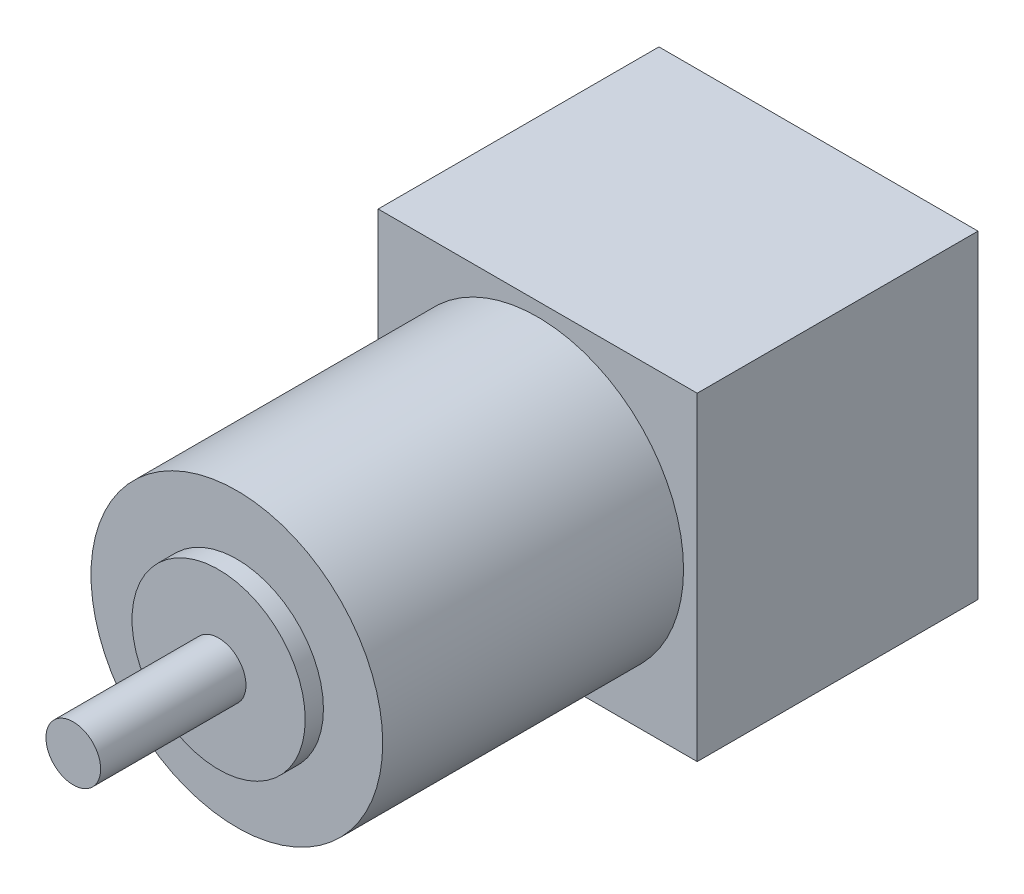
SolidWorks part; units mm, degrees
ref_plane "Front Plane" through (0, 0, 0) normal (0, 0, 1) x (1, 0, 0)
ref_plane "Top Plane" through (0, 0, 0) normal (0, 1, 0) x (1, 0, 0)
ref_plane "Right Plane" through (0, 0, 0) normal (1, 0, 0) x (0, 0, -1)
sketch "Sketch1" plane through (0, 0, 0) normal (0, 0, 1) x (1, 0, 0)
  line L1 (-17.5, -17.5) -> (17.5, -17.5)
  line L2 (-17.5, -17.5) -> (-17.5, 17.5)
  line L3 (-17.5, 17.5) -> (17.5, 17.5)
  line L4 (17.5, -17.5) -> (17.5, 17.5)
  line L5 (-17.5, -17.5) -> (17.5, 17.5) construction
  line L6 (-17.5, 17.5) -> (17.5, -17.5) construction
  point P0 (0, 0)
  dimension "D1" = 35
extrude "Boss-Extrude1" add sketch "Sketch1" along normal blind 30.8
sketch "Sketch2" plane through (0, 0, 30.8) normal (0, 0, 1) x (1, 0, 0)
  circle A0 centre (0, 0) radius 16
  dimension "D1" = 32
extrude "Boss-Extrude2" add sketch "Sketch2" along normal blind 33
sketch "Sketch4" plane through (0, 0, 63.8) normal (0, 0, 1) x (1, 0, 0)
  circle A0 centre (0, 0) radius 9.5
  dimension "D1" = 19
extrude "Boss-Extrude4" add sketch "Sketch4" along normal blind 2
sketch "Sketch3" plane through (0, 0, 65.8) normal (0, 0, 1) x (1, 0, 0)
  circle A0 centre (0, 0) radius 3
  dimension "D1" = 6
extrude "Boss-Extrude3" add sketch "Sketch3" along normal blind 15.94
